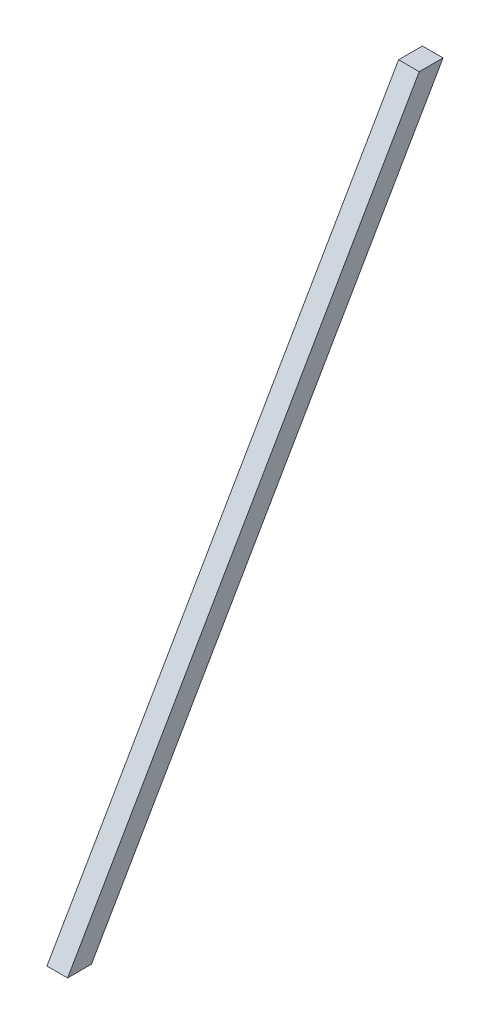
SolidWorks part; units mm, degrees
ref_plane "Front Plane" through (0, 0, 0) normal (0, 0, 1) x (1, 0, 0)
ref_plane "Top Plane" through (0, 0, 0) normal (0, 1, 0) x (1, 0, 0)
ref_plane "Right Plane" through (0, 0, 0) normal (1, 0, 0) x (0, 0, -1)
sketch "Sketch1" plane through (0, 0, 0) normal (1, 0, 0) x (0, 0, -1)
  line L0 (0, 0) -> (-29.3294, 0)
  line L1 (-29.3294, 0) -> (403.2792, 749.3)
  line L2 (403.2792, 749.3) -> (432.6086, 749.3)
  line L3 (432.6086, 749.3) -> (0, 0)
  line L4 (0, 0) -> (-21.997, 12.7) construction
  line L5 (0, 0) -> (793.4679, 0) construction
  line L7 (432.6086, 749.3) -> (432.6086, 0) construction
  point P4 (-21.997, 0)
  dimension "D1" = 25.4
  dimension "D2" = 749.3
  dimension "D3" = 60
extrude "Boss-Extrude1" add sketch "Sketch1" along normal blind 25.4
